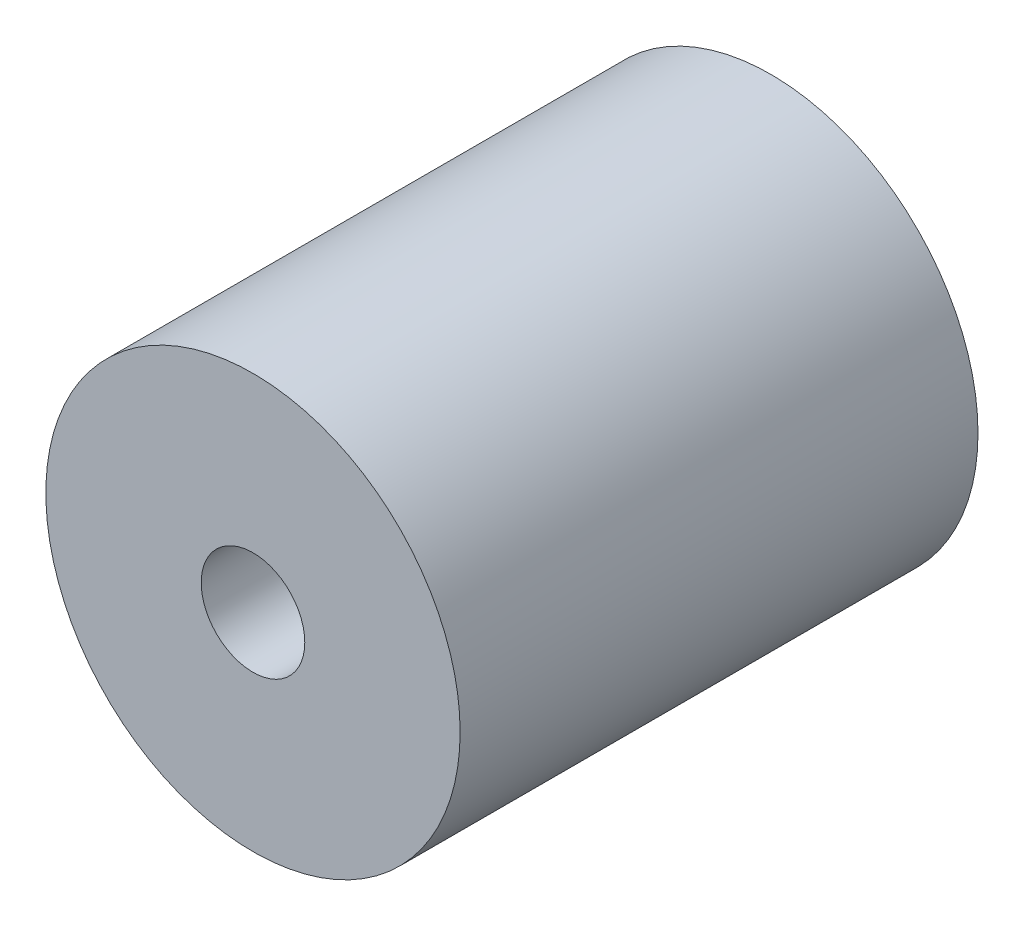
SolidWorks part; units mm, degrees
ref_plane "Front Plane" through (0, 0, 0) normal (0, 0, 1) x (1, 0, 0)
ref_plane "Top Plane" through (0, 0, 0) normal (0, 1, 0) x (1, 0, 0)
ref_plane "Right Plane" through (0, 0, 0) normal (1, 0, 0) x (0, 0, -1)
sketch "Sketch1" plane through (0, 0, 0) normal (0, 0, 1) x (1, 0, 0)
  circle A0 centre (0, 0) radius 10
  dimension "D1" = 20
extrude "Boss-Extrude1" add sketch "Sketch1" along normal blind 25
sketch "Sketch2" plane through (0, 0, 25) normal (0, 0, 1) x (1, 0, 0)
  circle A0 centre (0, 0) radius 2.5
  dimension "D1" = 5
extrude "Cut-Extrude1" cut sketch "Sketch2" against normal blind 6
sketch "Sketch3" plane through (0, 0, 0) normal (0, 0, -1) x (-1, 0, 0)
  circle A0 centre (0, 0) radius 3.175
  dimension "D1" = 6.35
extrude "Cut-Extrude2" cut sketch "Sketch3" against normal blind 6
